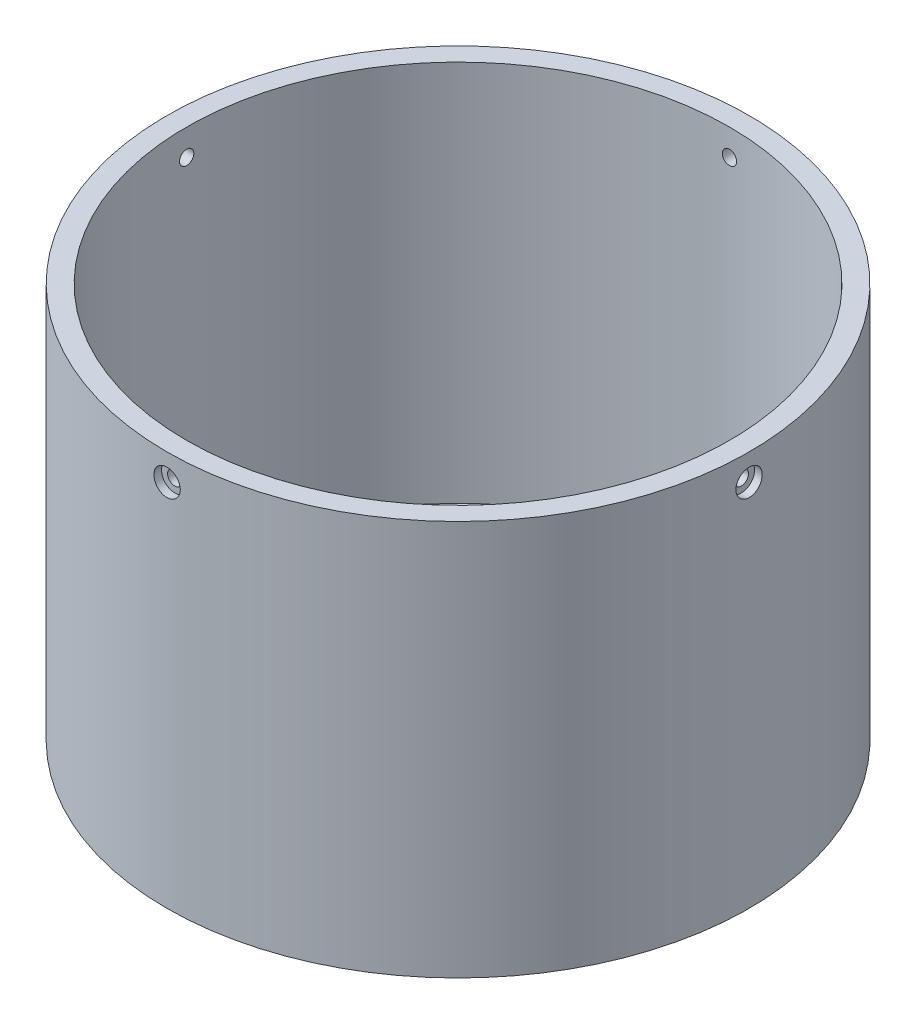
SolidWorks part; units mm, degrees
ref_plane "Piano frontale" through (0, 0, 0) normal (0, 0, 1) x (1, 0, 0)
ref_plane "Piano superiore" through (0, 0, 0) normal (0, 1, 0) x (1, 0, 0)
ref_plane "Piano destro" through (0, 0, 0) normal (1, 0, 0) x (0, 0, -1)
sketch "Schizzo1" plane through (0, 0, 0) normal (0, 1, 0) x (1, 0, 0)
  circle A0 centre (0, 0) radius 110.5
  circle A1 centre (0, 0) radius 103
  dimension "D1" = 221
  dimension "D2" = 7.5
extrude "Estrusione-Estrusione1" add sketch "Schizzo1" along normal blind 150
hole_wizard "Foro lamato per Bullone M12 a testa esagonale (Classe superiore)-1" positions "Schizzo3D1" profile "Schizzo3" counterbore size "M12" standard "DIN"
sketch3d "Schizzo3D1"
  line L0 (0, 0, 0) -> (0, 140, 0) construction
  line L2 (0, 140, 110.5) -> (0, 140, -110.5) construction
  line L4 (-110.5, 140, 0) -> (110.5, 140, 0) construction
  circle A0 centre (0, 140, 0) radius 110.5
  circle A1 centre (0, 150, 0) radius 110.5 construction
  point P0 (0, 140, 110.5)
  point P2 (110.5, 140, 0)
  point P4 (0, 140, -110.5)
  point P6 (-110.5, 140, 0)
  point P15 (0, 250.5, 0)
  point P19 (0, 260.5, 0)
  dimension "D1" = 140
sketch "Schizzo3" plane through (0, 140, 110.5) normal (1, 0, 0) x (0, -1, 0)
  line L0 (0, 0) -> (0, 9.7223)
  line L1 (0, 9.7223) -> (2.7, 8.1)
  line L2 (2.7, 8.1) -> (2.7, 3)
  line L3 (2.7, 3) -> (5, 3)
  line L4 (5, 3) -> (5, 0)
  line L5 (5, 0) -> (0, 0)
  line L10 (0, 9.7223) -> (-2.7, 8.1) construction
  line L11 (0, -6.35) -> (0, 107.95) construction
  dimension "Hole Dia." = 5.4
  dimension "Hole Depth" = 8.1
  dimension "C'Bore Dia." = 10
  dimension "C'Bore Depth" = 3
  dimension "Drill Angle" = 118
sketch "Schizzo4" plane through (0, 0, 0) normal (0, -1, 0) x (1, 0, 0)
  circle A0 centre (0, 0) radius 103
  circle A1 centre (0, 0) radius 73
  circle A2 centre (0, 0) radius 103 construction
  dimension "D1" = 30
extrude "Estrusione-Estrusione2" add sketch "Schizzo4" against normal blind 5
hole_wizard "Foro per Vite M6-1" positions "Schizzo5" profile "Schizzo6" hole size "M6" standard "DIN" end condition through all
sketch "Schizzo5" plane through (0, 5, 0) normal (0, 1, 0) x (1, 0, 0)
  circle A0 centre (0, 0) radius 88
  circle A1 centre (0, 0) radius 73 construction
  point P4 (-88, 0)
  point P6 (88, 0)
  point P8 (0, 88)
  point P10 (0, -88)
  dimension "D1" = 15
sketch "Schizzo6" plane through (0, 5, 88) normal (1, 0, 0) x (0, 0, 1)
  line L0 (0, 0) -> (0, 5)
  line L1 (0, 5) -> (3.3, 5)
  line L2 (3.3, 5) -> (3.3, 0)
  line L5 (3.3, 0) -> (0, 0)
  line L11 (0, -6.35) -> (0, 107.95) construction
  dimension "Thru Hole Dia." = 6.6
  dimension "Thru Hole Depth" = 5
